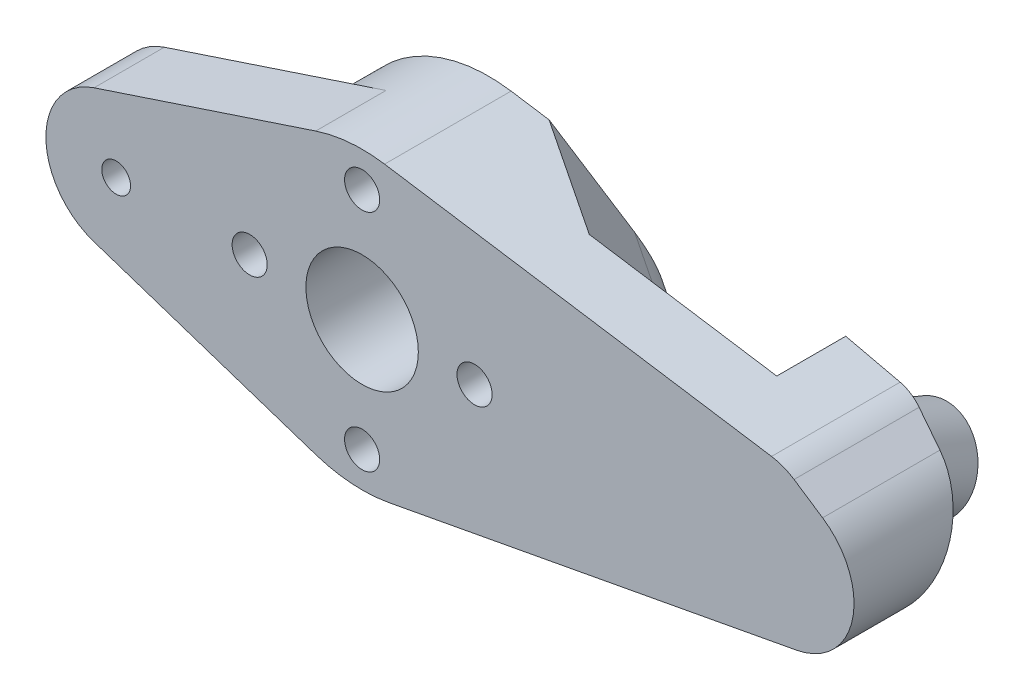
SolidWorks part; units mm, degrees
ref_plane "Plan de face" through (0, 0, 0) normal (0, 0, 1) x (1, 0, 0)
ref_plane "Plan de dessus" through (0, 0, 0) normal (0, 1, 0) x (1, 0, 0)
ref_plane "Plan de droite" through (0, 0, 0) normal (1, 0, 0) x (0, 0, -1)
sketch "Esquisse1" plane through (0, 0, 0) normal (0, 0, 1) x (1, 0, 0)
  line L1 (30.9167, -4.9153) -> (1.925, -10.322)
  line L2 (1.5995, 10.3775) -> (30, 6)
  line L3 (30, 6) -> (32.7639, 4.1667)
  arc A0 (1.5995, 10.3775) -> (1.925, -10.322) centre (0, 0) ccw
  arc A1 (32.7639, 4.1667) -> (30.9167, -4.9153) centre (30, 0) cw
  dimension "D1" = 10.5
  dimension "D2" = 5
  dimension "D3" = 30
  dimension "D4" = 6
extrude "Boss.-Extru.1" add sketch "Esquisse1" along normal blind 10
sketch "Esquisse2" plane through (0, 0, 10) normal (0, 0, 1) x (1, 0, 0)
  circle A0 centre (0, 0) radius 4
  circle A1 centre (0, 8) radius 1.25
  circle A2 centre (8, 0) radius 1.25
  circle A3 centre (0, -8) radius 1.25
  circle A4 centre (-8, 0) radius 1.25
  point P14 (0, 0)
  dimension "D1" = 2.5
  dimension "D2" = 8
  dimension "D3" = 8
  dimension "D4" = 4
extrude "Enlèv. mat.-Extru.1" cut sketch "Esquisse2" against normal up to next
sketch "Esquisse4" plane through (0, 0, 0) normal (0, 1, 0) x (1, 0, 0)
  line L0 (20, -5.5) -> (25, -5.5)
  line L1 (25, -5.5) -> (25, 0)
  line L2 (25, 0) -> (11, 0)
  line L3 (11, 0) -> (20, -5.5)
  line L5 (1.925, 0) -> (30.9167, 0) construction
  dimension "D1" = 11
  dimension "D2" = 9
  dimension "D3" = 5
  dimension "D4" = 5.5
extrude "Enlèv. mat.-Extru.2" cut sketch "Esquisse4" against normal up to next and the other way up to next
sketch "Esquisse5" plane through (0, 0, 0) normal (0, 0, -1) x (-1, 0, 0)
  line L3 (-25, -6.0187) -> (-25, 6.7707)
  line L4 (-25, 6.7707) -> (-30, 6)
  line L5 (-30.9167, -4.9153) -> (-25, -6.0187)
  line L6 (-25, -6.0187) -> (-25, 6.7707)
  line L8 (-30.9167, -4.9153) -> (-25, -6.0187)
  line L10 (-25, 6.7707) -> (-30, 6)
  line L11 (-30, 6) -> (-32.7639, 4.1667)
  line L12 (-30, 6) -> (-32.7639, 4.1667)
  arc A1 (-32.7639, 4.1667) -> (-30.9167, -4.9153) centre (-30, 0) ccw
  arc A2 (-32.7639, 4.1667) -> (-30.9167, -4.9153) centre (-30, 0) ccw
  dimension "D1" = 0
extrude "Boss.-Extru.2" add sketch "Esquisse5" along normal blind 2
sketch "Esquisse6" plane through (25, 0, 0) normal (-1, 0, 0) x (0, 0, 1)
  line L0 (-2, 6.7707) -> (3.214, -6.0187)
  line L1 (-2, -6.0187) -> (5.5, -6.0187) construction
  line L2 (3.214, -6.0187) -> (-2, -6.0187)
  line L3 (-2, -6.0187) -> (-2, 6.7707)
  line L4 (-2, -6.0187) -> (-2, 6.7707) construction
  dimension "D1" = 22.18
extrude "Enlèv. mat.-Extru.3" cut sketch "Esquisse6" against normal up to next
sketch "Esquisse7" plane through (0, 0.2658, 0.6519) normal (0, -0.3775, -0.926) x (-1, 0, 0)
  line L0 (8, 0) -> (-34.9929, 0) construction
  line L1 (-25, -6.7867) -> (-25, 7.0247) construction
  circle A0 centre (-30, 1.25) radius 1.25
  ellipse E0 centre (8, 0) end of major axis (9.25, 0) minor radius 1.1575 construction
  ellipse E1 centre (-8, 0) end of major axis (-6.75, 0) minor radius 1.1575 construction
  ellipse E2 centre (8, 0) end of major axis (9.25, 0) minor radius 1.1575 construction
  ellipse E3 centre (-8, 0) end of major axis (-6.75, 0) minor radius 1.1575 construction
  ellipse E4 centre (-30, -0.287) end of major axis (-30, 5.1125) minor radius 5 (-32.7639, 4.2126) -> (-30.9167, -5.5951) ccw construction
  dimension "D2" = 2.5
  dimension "D1" = 5
  dimension "D3" = 1.25
extrude "Enlèv. mat.-Extru.4" cut sketch "Esquisse7" against normal blind 6
sketch "Esquisse8" plane through (0, 0.2658, 0.6519) normal (0, -0.3775, -0.926) x (-1, 0, 0)
  line L0 (-25, -10.8272) -> (-25, 10.9138)
  line L1 (-25, 10.9138) -> (-38.8482, 10.9138)
  line L2 (-38.8482, 10.9138) -> (-38.8482, -10.8272)
  line L3 (-38.8482, -10.8272) -> (-25, -10.8272)
  line L4 (-25, -6.7867) -> (-25, 7.0247) construction
extrude "Enlèv. mat.-Extru.5" cut sketch "Esquisse8" against normal blind 2.4
sketch "Esquisse9" plane through (0, 1.1718, 2.8743) normal (0, -0.3775, -0.926) x (-1, 0, 0)
  line L1 (-30, 5.214) -> (-32.7639, 3.2342) construction
  circle A0 centre (-30, 1.25) radius 3.2225
  circle A1 centre (-30, 1.25) radius 1.25 construction
  circle A2 centre (-30, 1.25) radius 1.25
extrude "Boss.-Extru.3" add sketch "Esquisse9" along normal blind 3
chamfer "Chanfrein1" distance 4 angle 45 2 edges at (15.5, -7.7904, 2.75) (15.5, 8.2349, 2.75)
fillet "Congé1" radius 4 3 edges at (15.5, -3.2891, 2.75) (30, 6, 5.453) (15.5, 4.2005, 2.75)
sketch "Esquisse10" plane through (0, 0, 0) normal (0, 0, -1) x (-1, 0, 0)
  circle A4 centre (0, 0) radius 15.6017
extrude "Enlèv. mat.-Extru.6" cut sketch "Esquisse10" against normal blind 1
sketch "Esquisse13" plane through (0, 0, 10) normal (0, 0, 1) x (1, 0, 0)
  line L0 (-3.3, -9.9679) -> (-19.0714, -4.7466)
  line L1 (0, 0) -> (-17.5, 0) construction
  line L2 (-19.0714, 4.7466) -> (-3.3, 9.9679)
  arc A0 (1.5995, 10.3775) -> (1.925, -10.322) centre (0, 0) ccw construction
  arc A1 (-19.0714, -4.7466) -> (-19.0714, 4.7466) centre (-17.5, 0) cw
  arc A2 (-3.3, -9.9679) -> (-3.3, 9.9679) centre (0, 0) cw
  circle A3 centre (-17.5, 0) radius 1.025
  dimension "D2" = 2.05
  dimension "D3" = 5
  dimension "D1" = 17.5
extrude "Boss.-Extru.5" add sketch "Esquisse13" against normal blind 5
sketch "Esquisse14" plane through (-3.3, -9.9679, 0) normal (-0.3143, -0.9493, 0) x (0.9493, -0.3143, 0)
  line L0 (-16.6132, 5) -> (-16.6132, 10) construction
  line L1 (-16.6132, 5) -> (0, 5) construction
  text T0 "<b>M2.5</b>"
  dimension "D1" = 1
  dimension "D2" = 0.75
extrude "Enlèv. mat.-Extru.7" cut sketch "Esquisse14" against normal blind 1.5
